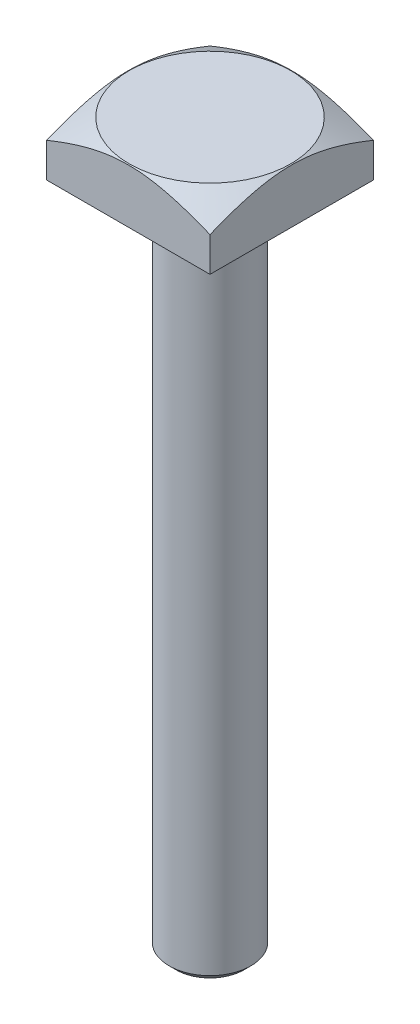
SolidWorks part; units mm, degrees
ref_plane "Front Plane" through (0, 0, 0) normal (0, 0, 1) x (1, 0, 0)
ref_plane "Top Plane" through (0, 0, 0) normal (0, 1, 0) x (1, 0, 0)
ref_plane "Right Plane" through (0, 0, 0) normal (1, 0, 0) x (0, 0, -1)
sketch "Sketch1" plane through (0, 0, 0) normal (0, 1, 0) x (1, 0, 0)
  line L1 (-12, 12) -> (12, 12)
  line L2 (-12, 12) -> (-12, -12)
  line L3 (-12, -12) -> (12, -12)
  line L4 (12, 12) -> (12, -12)
  line L5 (-12, 12) -> (12, -12) construction
  line L6 (-12, -12) -> (12, 12) construction
  point P0 (0, 0)
  dimension "D1" = 24
  dimension "D2" = 24
extrude "Boss-Extrude1" add sketch "Sketch1" along normal blind 8
sketch "Sketch2" plane through (0, 8, 0) normal (0, 1, 0) x (1, 0, 0)
  circle A1 centre (0, 0) radius 11.8741
extrude "Cut-Extrude1" cut sketch "Sketch2" against normal blind 8 draft 60 flip side to cut
sketch "Sketch3" plane through (0, 0, 0) normal (0, -1, 0) x (1, 0, 0)
  circle A0 centre (0, 0) radius 6
  dimension "D1" = 12
extrude "Boss-Extrude2" add sketch "Sketch3" along normal blind 98
chamfer "Chamfer1" distance 1 angle 45 1 edges at (0, -98, -6)
